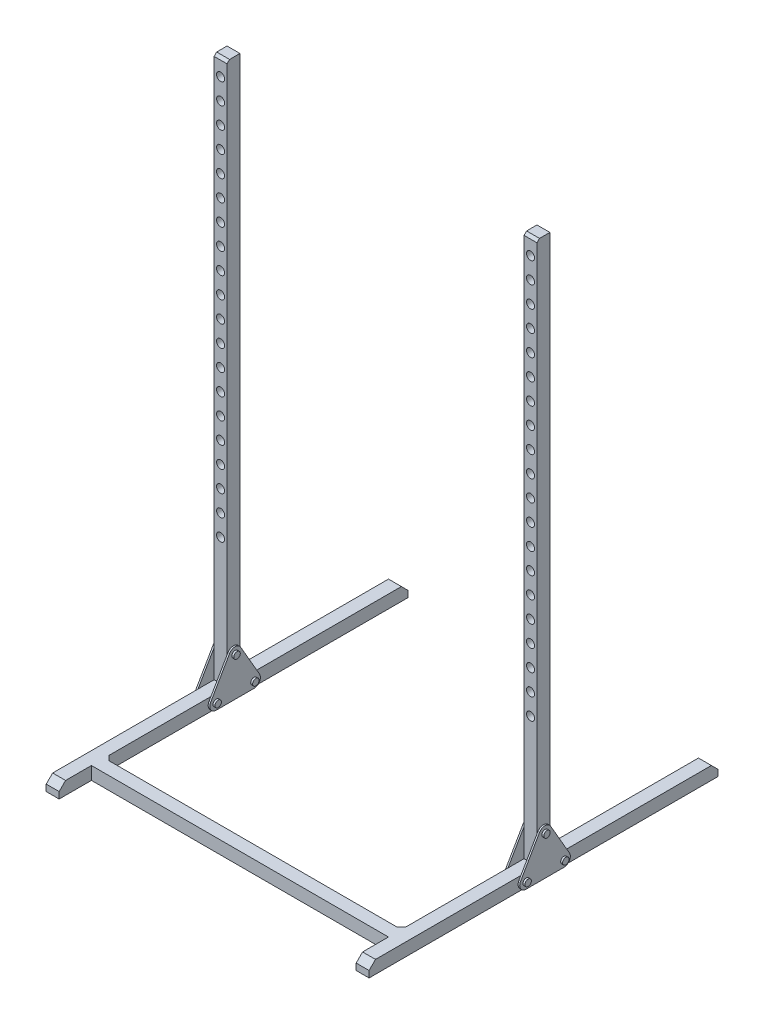
SolidWorks part; units mm, degrees
ref_plane "Front Plane" through (0, 0, 0) normal (0, 0, 1) x (1, 0, 0)
ref_plane "Top Plane" through (0, 0, 0) normal (0, 1, 0) x (1, 0, 0)
ref_plane "Right Plane" through (0, 0, 0) normal (1, 0, 0) x (0, 0, -1)
sketch "Sketch1" plane through (0, 0, 0) normal (0, 0, 1) x (1, 0, 0)
  line L1 (-25.4, 25.4) -> (25.4, 25.4)
  line L2 (-25.4, 25.4) -> (-25.4, -25.4)
  line L3 (-25.4, -25.4) -> (25.4, -25.4)
  line L4 (25.4, 25.4) -> (25.4, -25.4)
  line L5 (-25.4, 25.4) -> (25.4, -25.4) construction
  line L6 (-25.4, -25.4) -> (25.4, 25.4) construction
  point P0 (0, 0)
  dimension "D1" = 50.8
  dimension "D2" = 50.8
extrude "Boss-Extrude1" add sketch "Sketch1" along normal blind 1371.6
sketch "Sketch2" plane through (25.4, 0, 0) normal (1, 0, 0) x (0, 0, -1)
  line L0 (-1371.6, -25.4) -> (0, -25.4) construction
  line L1 (-1244.6284, 25.4) -> (-1193.8284, 25.4)
  line L2 (-1244.6284, 25.4) -> (-1244.6284, -25.4)
  line L3 (-1244.6284, -25.4) -> (-1193.8284, -25.4)
  line L4 (-1193.8284, 25.4) -> (-1193.8284, -25.4)
  line L5 (-1244.6284, 25.4) -> (-1193.8284, -25.4) construction
  line L6 (-1244.6284, -25.4) -> (-1193.8284, 25.4) construction
  point P0 (-1219.2284, 0)
  dimension "D1" = 50.8
extrude "Boss-Extrude2" add sketch "Sketch2" along normal blind 1168.4
ref_plane "Plane1" through (609.6, 0, 0) normal (1, 0, 0) x (0, 0, -1)
mirror "Mirror1" about plane through (609.6, 0, 0) normal (1, 0, 0) of "Boss-Extrude1"
sketch "Sketch3" plane through (0, 25.4, 0) normal (0, 1, 0) x (1, 0, 0)
  line L0 (25.4, -1193.8284) -> (25.4, 0) construction
  line L1 (-25.4, -660.4) -> (25.4, -660.4)
  line L2 (-25.4, -660.4) -> (-25.4, -711.2)
  line L3 (-25.4, -711.2) -> (25.4, -711.2)
  line L4 (25.4, -660.4) -> (25.4, -711.2)
  line L5 (-25.4, -660.4) -> (25.4, -711.2) construction
  line L6 (-25.4, -711.2) -> (25.4, -660.4) construction
  point P0 (0, -685.8)
  dimension "D1" = 50.8
  dimension "D2" = 660.4
extrude "Boss-Extrude3" add sketch "Sketch3" along normal blind 2133.6
sketch "Sketch4" plane through (-25.4, 0, 0) normal (-1, 0, 0) x (0, 0, 1)
  line L0 (567.6847, -25.4) -> (685.8, 179.1817)
  line L1 (1371.6, -25.4) -> (0, -25.4) construction
  line L2 (685.8, 179.1817) -> (803.9153, -25.4)
  line L3 (803.9153, -25.4) -> (567.6847, -25.4)
  line L5 (660.4, 179.1817) -> (711.2, 179.1817)
  line L6 (660.4, 2159) -> (660.4, 25.4) construction
  line L7 (711.2, 2159) -> (711.2, 25.4) construction
  point P8 (685.8, 179.1817)
  line M5 (0, -25.4) -> (1371.6, -25.4)
  line M7 (1371.6, 25.4) -> (711.2, 25.4)
  line M8 (711.2, 25.4) -> (711.2, 2159)
  line M10 (660.4, 2159) -> (660.4, 25.4)
  line M11 (660.4, 25.4) -> (0, 25.4)
extrude "Boss-Extrude4" add sketch "Sketch4" along normal blind 6.35 contours L2 L0 M10 M11 M5 M7 M8 | L0 M11 M10 | L2 M8 M7
fillet "Fillet1" radius 25.4 3 edges at (-28.575, -25.4, 803.9153) (-28.575, 179.1817, 685.8) (-28.575, -25.4, 567.6847)
ref_plane "Plane2" through (0, 0, 0) normal (1, 0, 0) x (0, 0, -1)
mirror "Mirror2" about plane through (0, 0, 0) normal (1, 0, 0) of "Boss-Extrude4"
fillet "Fillet2" radius 25.4 3 edges at (28.575, 179.1817, 685.8) (28.575, -25.4, 803.9153) (28.575, -25.4, 567.6847)
mirror "Mirror4" about plane through (609.6, 0, 0) normal (1, 0, 0) of "Mirror2", "Boss-Extrude3", "Boss-Extrude4"
fillet "Fillet3" radius 25.4 6 edges at (1247.775, 179.1817, 685.8) (1247.775, -25.4, 803.9153) (1247.775, -25.4, 567.6847) (1190.625, -25.4, 803.9153) (1190.625, 179.1817, 685.8) (1190.625, -25.4, 567.6847)
chamfer "Chamfer1" distance 25.24 angle 45 4 edges at (1219.2, 25.4, 1371.6) (1219.2, 25.4, 0) (0, 25.4, 0) (0, 25.4, 1371.6)
chamfer "Chamfer2" distance 17.62 angle 45 2 edges at (25.4, 0, 1193.8284) (1193.8, 0, 1193.8284)
sketch "Sketch7" plane through (0, 0, 660.4) normal (0, 0, -1) x (-1, 0, 0)
  line L0 (-25.4, 2159) -> (25.4, 2159) construction
  circle A0 centre (0, 2092.325) radius 15.875
  dimension "D1" = 31.75
  dimension "D2" = 50.8
extrude "Cut-Extrude1" cut sketch "Sketch7" against normal through all
pattern_linear "LPattern1" count 20 spacing 82.55 along (0, -1, 0) of "Cut-Extrude1"
mirror "Mirror5" about plane through (609.6, 0, 0) normal (1, 0, 0) of "LPattern1", "Cut-Extrude1"
sketch "Sketch8" plane through (-31.75, 0, 0) normal (-1, 0, 0) x (0, 0, 1)
  circle A0 centre (685.8, 128.3817) radius 12.7
  circle A1 centre (611.6788, 0) radius 12.7
  circle A2 centre (759.9212, 0) radius 12.7
  dimension "D1" = 25.4
  dimension "D2" = 25.4
  dimension "D3" = 25.4
extrude "Boss-Extrude5" add sketch "Sketch8" along normal blind 7.62
mirror "Mirror6" about plane through (0, 0, 0) normal (1, 0, 0) of "Boss-Extrude5"
mirror "Mirror7" about plane through (609.6, 0, 0) normal (1, 0, 0) of "Mirror6", "Boss-Extrude5"
chamfer "Chamfer3" distance 10 angle 45 2 edges at (0, 2159, 711.2) (1219.2, 2159, 711.2)
